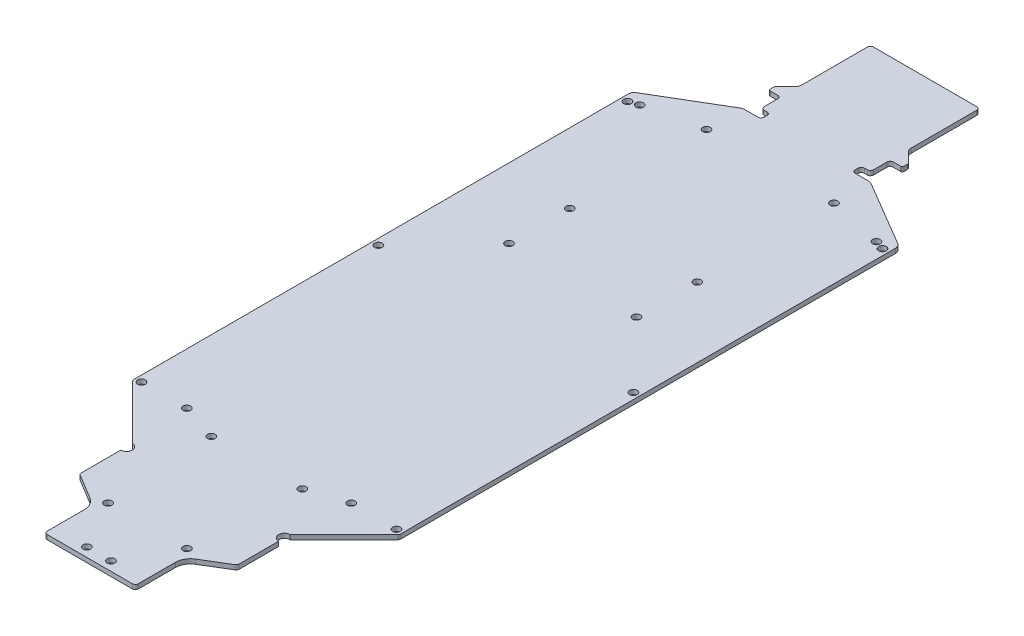
SolidWorks part; units mm, degrees
ref_plane "Front Plane" through (0, 0, 0) normal (0, 0, 1) x (1, 0, 0)
ref_plane "Top Plane" through (0, 0, 0) normal (0, 1, 0) x (1, 0, 0)
ref_plane "Right Plane" through (0, 0, 0) normal (1, 0, 0) x (0, 0, -1)
sketch "Sketch2" plane through (0, 0, 0) normal (0, 1, 0) x (1, 0, 0)
  line L3 (44, -37.7267) -> (44, -200.5858)
  line L4 (14.0226, -259) -> (-13.9774, -259)
  line L7 (15.0226, -258) -> (15.0226, -245.8193)
  line L9 (26, -235.7967) -> (26, -222.7896)
  line L10 (17.4349, -241.5409) -> (25.5175, -236.6523)
  line L13 (26, -219) -> (43.7071, -201.2929)
  line L16 (-16.9774, 16) -> (17.0226, 16)
  line L17 (18.0226, 15) -> (18.0226, -6.6786)
  line L18 (17.0226, -20) -> (16.0226, -20)
  line L19 (15.0226, -21) -> (15.0226, -22)
  line L21 (16.0226, -23) -> (20.4756, -23)
  line L22 (21.4935, -23.2784) -> (43.0179, -36.0051)
  line L23 (19.0226, -13.507) -> (21.5226, -13.507)
  line L24 (22.0226, -13.007) -> (22.0226, -11.9212)
  line L25 (21.7297, -11.2141) -> (18.6084, -8.0928)
  line L26 (18.0226, -14.507) -> (18.0226, -19)
  line L27 (-17.9774, -14.507) -> (-17.9774, -19)
  line L28 (-21.6845, -11.2141) -> (-18.5632, -8.0928)
  line L29 (-21.9774, -13.007) -> (-21.9774, -11.9212)
  line L30 (-18.9774, -13.507) -> (-21.4774, -13.507)
  line L31 (-21.4483, -23.2784) -> (-42.9727, -36.0051)
  line L33 (-15.9774, -23) -> (-20.4304, -23)
  line L34 (-14.9774, -21) -> (-14.9774, -22)
  line L35 (-16.9774, -20) -> (-15.9774, -20)
  line L37 (0.0226, -259) -> (0.0226, 16)
  line L38 (-17.9774, 15) -> (-17.9774, -6.6786)
  line L40 (-25.9548, -219) -> (-43.6619, -201.2929)
  line L41 (-17.3897, -241.5409) -> (-25.4723, -236.6523)
  line L42 (-25.9548, -235.7967) -> (-25.9548, -222.7896)
  line L43 (-14.9774, -258) -> (-14.9774, -245.8193)
  line L44 (-43.9548, -37.7267) -> (-43.9548, -200.5858)
  circle A1 centre (42, -200) radius 1.25
  circle A3 centre (27.0913, -200) radius 1.25
  circle A8 centre (4, -256) radius 1.25
  circle A9 centre (13, -240) radius 1.25
  circle A10 centre (15, -204) radius 1.25
  circle A12 centre (42, -40) radius 1.25
  arc A13 (17.4349, -241.5409) -> (15.0226, -245.8193) centre (20.0226, -245.8193) ccw
  arc A14 (26, -219) -> (26, -222.7896) centre (26, -220.8948) ccw
  arc A15 (15.0226, -258) -> (14.0226, -259) centre (14.0226, -258) cw
  arc A16 (26, -235.7967) -> (25.5175, -236.6523) centre (25, -235.7967) cw
  arc A17 (44, -200.5858) -> (43.7071, -201.2929) centre (43, -200.5858) cw
  circle A18 centre (39, -39) radius 1.25
  circle A19 centre (21, -35) radius 1.25
  circle A20 centre (42, -122) radius 1.25
  circle A21 centre (21, -100) radius 1.25
  circle A22 centre (21, -80) radius 1.25
  arc A23 (43.0179, -36.0051) -> (44, -37.7267) centre (42, -37.7267) cw
  arc A24 (20.4756, -23) -> (21.4935, -23.2784) centre (20.4756, -25) cw
  arc A25 (16.0226, -23) -> (15.0226, -22) centre (16.0226, -22) cw
  arc A26 (16.0226, -20) -> (15.0226, -21) centre (16.0226, -21) ccw
  arc A27 (18.0226, -19) -> (17.0226, -20) centre (17.0226, -19) cw
  arc A28 (17.0226, 16) -> (18.0226, 15) centre (17.0226, 15) cw
  arc A29 (19.0226, -13.507) -> (18.0226, -14.507) centre (19.0226, -14.507) ccw
  arc A30 (21.5226, -13.507) -> (22.0226, -13.007) centre (21.5226, -13.007) ccw
  arc A31 (18.6084, -8.0928) -> (18.0226, -6.6786) centre (20.0226, -6.6786) cw
  arc A32 (22.0226, -11.9212) -> (21.7297, -11.2141) centre (21.0226, -11.9212) ccw
  arc A33 (-21.9774, -11.9212) -> (-21.6845, -11.2141) centre (-20.9774, -11.9212) cw
  arc A34 (-18.5632, -8.0928) -> (-17.9774, -6.6786) centre (-19.9774, -6.6786) ccw
  arc A35 (-21.4774, -13.507) -> (-21.9774, -13.007) centre (-21.4774, -13.007) cw
  arc A36 (-18.9774, -13.507) -> (-17.9774, -14.507) centre (-18.9774, -14.507) cw
  arc A37 (-16.9774, 16) -> (-17.9774, 15) centre (-16.9774, 15) ccw
  arc A38 (-17.9774, -19) -> (-16.9774, -20) centre (-16.9774, -19) ccw
  arc A39 (-15.9774, -20) -> (-14.9774, -21) centre (-15.9774, -21) cw
  arc A40 (-15.9774, -23) -> (-14.9774, -22) centre (-15.9774, -22) ccw
  arc A41 (-20.4304, -23) -> (-21.4483, -23.2784) centre (-20.4304, -25) ccw
  arc A42 (-42.9727, -36.0051) -> (-43.9548, -37.7267) centre (-41.9548, -37.7267) ccw
  circle A43 centre (-20.9548, -80) radius 1.25
  circle A44 centre (-20.9548, -100) radius 1.25
  circle A45 centre (-41.9548, -122) radius 1.25
  circle A46 centre (-20.9548, -35) radius 1.25
  circle A47 centre (-38.9548, -39) radius 1.25
  arc A48 (-43.9548, -200.5858) -> (-43.6619, -201.2929) centre (-42.9548, -200.5858) ccw
  arc A49 (-25.9548, -235.7967) -> (-25.4723, -236.6523) centre (-24.9548, -235.7967) ccw
  arc A50 (-14.9774, -258) -> (-13.9774, -259) centre (-13.9774, -258) ccw
  arc A51 (-25.9548, -219) -> (-25.9548, -222.7896) centre (-25.9548, -220.8948) cw
  arc A52 (-17.3897, -241.5409) -> (-14.9774, -245.8193) centre (-19.9774, -245.8193) cw
  circle A53 centre (-41.9548, -40) radius 1.25
  circle A54 centre (-14.9548, -204) radius 1.25
  circle A55 centre (-12.9548, -240) radius 1.25
  circle A56 centre (-3.9548, -256) radius 1.25
  circle A57 centre (-27.0461, -200) radius 1.25
  circle A58 centre (-41.9548, -200) radius 1.25
  point P28 (44, -36.5858)
  point P65 (18.0226, -13.507)
  point P68 (0, 0)
  point P140 (-17.9774, -13.507)
  point P141 (-43.9548, -36.5858)
  dimension "D8" = 1
  dimension "D9" = 10
  dimension "D10" = 2
  dimension "D11" = 2
  dimension "D12" = 2
  dimension "D13" = 1
  dimension "D14" = 1
  dimension "D15" = 16
  dimension "D16" = 18
  dimension "D17" = 34
  dimension "D18" = 15
  dimension "D19" = 2.5
  dimension "D20" = 2.5
  dimension "D27" = 2.5
  dimension "D31" = 43.9774
  dimension "D35" = 2.5
  dimension "D37" = 0.0226
  dimension "D40" = 38.9774
  dimension "D41" = 59.406
  dimension "D42" = 2
  dimension "D43" = 3.9568
  dimension "D58" = 19
  dimension "D61" = 2.5
  dimension "D64" = 116
  dimension "D65" = 2.5
  dimension "D66" = 2
  dimension "D67" = 2.1213
  dimension "D68" = 1
  dimension "D69" = 0.5
  dimension "D4" = 2
  dimension "D5" = 2
  dimension "D7" = 1
  dimension "D29" = 4.6229
  dimension "D45" = 2.5
  dimension "D46" = 20
  dimension "D47" = 2.5
  dimension "D48" = 23
  dimension "D49" = 21
  dimension "D50" = 2.5
  dimension "D51" = 2
  dimension "D52" = 78
  dimension "D53" = 2.084
  dimension "D54" = 14.9087
  dimension "D55" = 36
  dimension "D59" = 2.5
  dimension "D60" = 2.5
  dimension "D62" = 3
  dimension "D63" = 3.9774
  dimension "D70" = 2
  dimension "D71" = 1
  dimension "D21" = 164
  dimension "D22" = 12.1807
  dimension "D23" = 9.446
  dimension "D24" = 13.0071
  dimension "D25" = 275
  dimension "D26" = 14
  dimension "D28" = 10.341
  dimension "D30" = 25.0054
  dimension "D32" = 3
  dimension "D33" = 12.6634
  dimension "D34" = 12.0913
  dimension "D36" = 15
  dimension "D38" = 20.9774
  dimension "D39" = 25.0416
  dimension "D44" = 23
  dimension "D56" = 25.9774
  dimension "D57" = 12.9774
  dimension "D72" = 2.5
  dimension "D73" = 3.1213
  dimension "D74" = 9.493
  dimension "D75" = 11.9072
extrude "Boss-Extrude1" add sketch "Sketch2" along normal blind 1.5 contours L24 A32 L25 A31 L17 A28 L16 L37 L4 A15 L7 A13 L10 A16 L9 A14 L13 A17 L3 A23 L22 A24 L21 A25 L19 A26 L18 A27 L26 A29 L23 A30 A1 A3 A8 A9 A10 A12 A18 A19 A20 | L41 A52 L43 A50 L4 L37 L16 A37 L38 A34 L28 A33 L29 A35 L30 A36 L27 A38 L35 A39 L34 A40 L33 A41 L31 A42 L44 A48 L40 A51 L42 A49 A57 A55 A53 A47 A45 A43 A44 A46 A54
